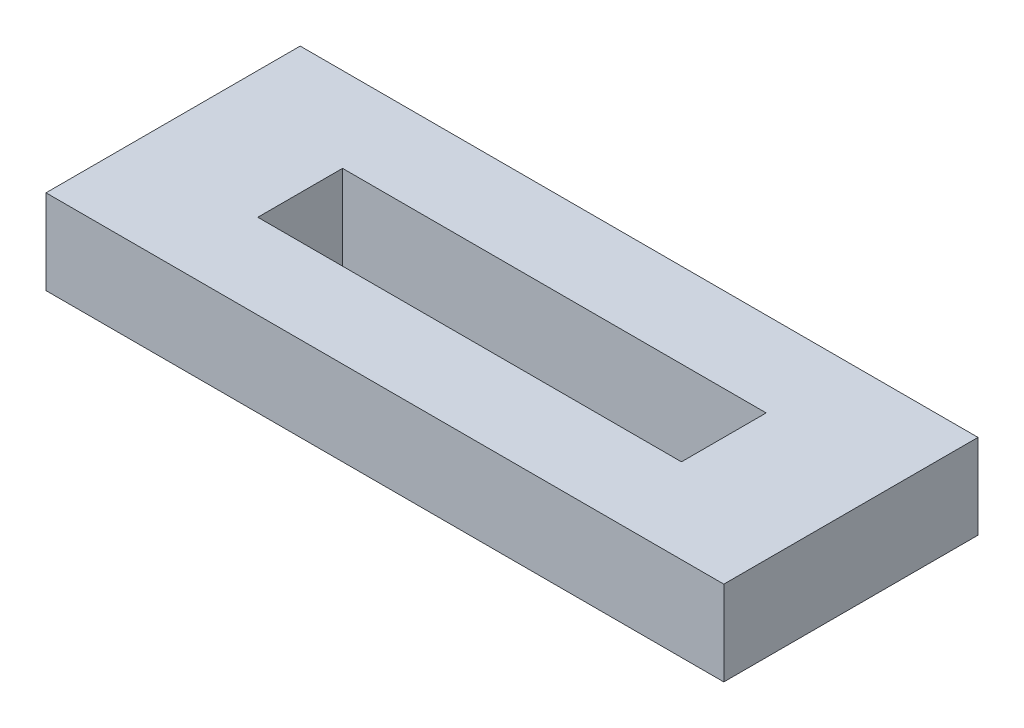
SolidWorks part; units mm, degrees
ref_plane "Front Plane" through (0, 0, 0) normal (0, 0, 1) x (1, 0, 0)
ref_plane "Top Plane" through (0, 0, 0) normal (0, 1, 0) x (1, 0, 0)
ref_plane "Right Plane" through (0, 0, 0) normal (1, 0, 0) x (0, 0, -1)
sketch "Sketch1" plane through (0, 0, 0) normal (0, 1, 0) x (1, 0, 0)
  line L0 (-28.5782, 0) -> (27.7725, 0) construction
  line L1 (0, 16.7536) -> (0, -13.5308) construction
  line L3 (-25, 5) -> (25, 5)
  line L4 (-25, 5) -> (-25, -5)
  line L5 (-25, -5) -> (25, -5)
  line L6 (25, 5) -> (25, -5)
  line L7 (-25, 5) -> (25, -5) construction
  line L8 (-25, -5) -> (25, 5) construction
  line L9 (-40, 15) -> (40, 15)
  line L10 (-40, 15) -> (-40, -15)
  line L11 (-40, -15) -> (40, -15)
  line L12 (40, 15) -> (40, -15)
  line L13 (-40, 15) -> (40, -15) construction
  line L14 (-40, -15) -> (40, 15) construction
  point P5 (0, 0)
  point P10 (0, 0)
  dimension "D1" = 10
  dimension "D2" = 30
  dimension "D3" = 50
  dimension "D4" = 80
extrude "Boss-Extrude1" add sketch "Sketch1" along normal blind 10
